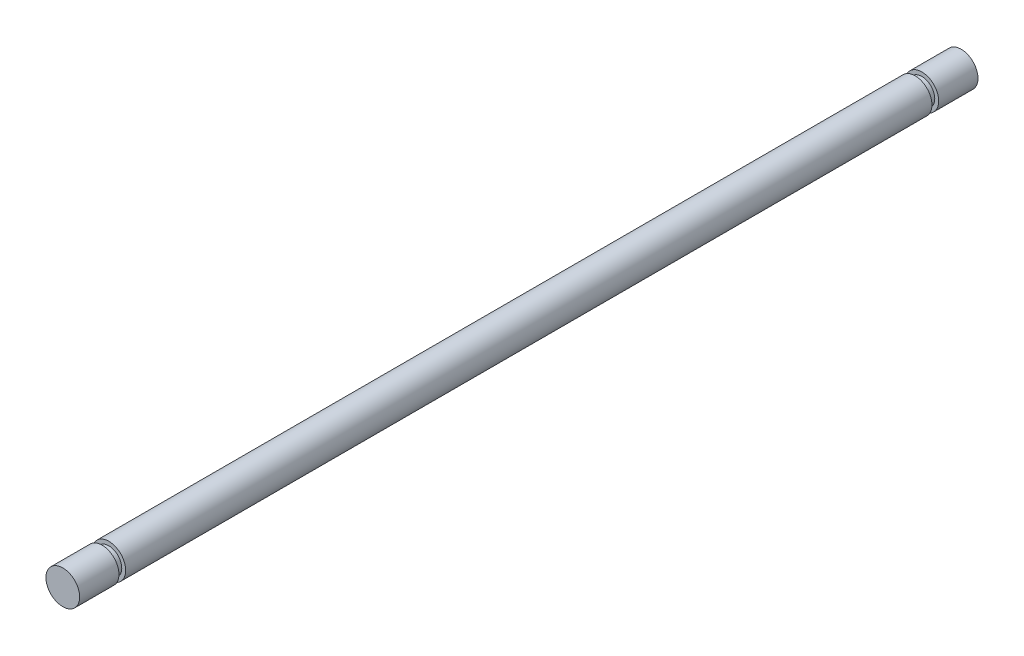
SolidWorks part; units mm, degrees
ref_plane "前视基准面" through (0, 0, 0) normal (0, 0, 1) x (1, 0, 0)
ref_plane "上视基准面" through (0, 0, 0) normal (0, 1, 0) x (1, 0, 0)
ref_plane "右视基准面" through (0, 0, 0) normal (1, 0, 0) x (0, 0, -1)
other "Configuration Table"
sketch "草图1" plane through (0, 0, 0) normal (0, 0, 1) x (1, 0, 0)
  circle A0 centre (0, 0) radius 1.5
extrude "凸台-拉伸1" add sketch "草图1" along normal blind 3.5
sketch "草图2" plane through (0, 0, 3.5) normal (0, 0, 1) x (1, 0, 0)
  circle A0 centre (0, 0) radius 1.15
extrude "凸台-拉伸2" add sketch "草图2" along normal blind 0.6
sketch "草图3" plane through (0, 0, 4.1) normal (0, 0, 1) x (1, 0, 0)
  circle A0 centre (0, 0) radius 1.5
extrude "凸台-拉伸3" add sketch "草图3" along normal blind 71.8
sketch "草图4" plane through (0, 0, 75.9) normal (0, 0, 1) x (1, 0, 0)
  circle A0 centre (0, 0) radius 1.15
extrude "凸台-拉伸4" add sketch "草图4" along normal blind 0.6
sketch "草图5" plane through (0, 0, 76.5) normal (0, 0, 1) x (1, 0, 0)
  circle A0 centre (0, 0) radius 1.5
extrude "凸台-拉伸5" add sketch "草图5" along normal blind 3.5
